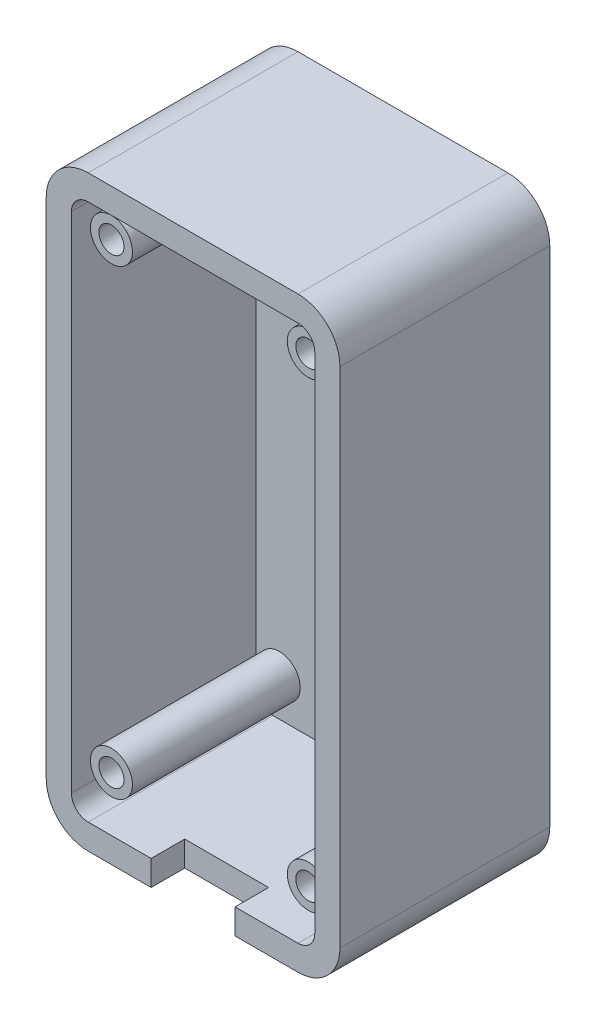
SolidWorks part; units mm, degrees
ref_plane "前视基准面" through (0, 0, 0) normal (0, 0, 1) x (1, 0, 0)
ref_plane "上视基准面" through (0, 0, 0) normal (0, 1, 0) x (1, 0, 0)
ref_plane "右视基准面" through (0, 0, 0) normal (1, 0, 0) x (0, 0, -1)
sketch "草图1" plane through (0, 0, 0) normal (0, 0, 1) x (1, 0, 0)
  line L1 (-193.4252, 70) -> (-168.4252, 70)
  line L2 (-198.4252, 65) -> (-198.4252, 5)
  line L3 (-193.4252, 0) -> (-168.4252, 0)
  line L4 (-163.4252, 65) -> (-163.4252, 5)
  line L5 (-198.4252, 70) -> (-163.4252, 0) construction
  line L6 (-198.4252, 0) -> (-163.4252, 70) construction
  arc A0 (-198.4252, 5) -> (-193.4252, 0) centre (-193.4252, 5) ccw
  arc A1 (-168.4252, 0) -> (-163.4252, 5) centre (-168.4252, 5) ccw
  arc A2 (-168.4252, 70) -> (-163.4252, 65) centre (-168.4252, 65) cw
  arc A3 (-193.4252, 70) -> (-198.4252, 65) centre (-193.4252, 65) ccw
  point P0 (-180.9252, 35)
  dimension "D3" = 5
  dimension "D1" = 70
  dimension "D2" = 35
extrude "凸台-拉伸1" add sketch "草图1" along normal blind 25
shell "抽壳2" thickness 3
sketch "草图3" plane through (0, 0, 3) normal (0, 0, 1) x (1, 0, 0)
  line L0 (-124.8248, 35) -> (-208.0256, 35) construction
  line L1 (-180.9252, 64.1908) -> (-180.9252, 32.4467) construction
  circle A0 centre (-192.6567, 62.5) radius 2.5
  circle A1 centre (-192.6567, 7.5) radius 2.5
  circle A2 centre (-169.1937, 62.5) radius 2.5
  circle A3 centre (-169.1937, 7.5) radius 2.5
  point P13 (-166.4252, 35)
  point P14 (-166.4252, 35)
  dimension "D1" = 5
  dimension "D2" = 55
extrude "凸台-拉伸4" add sketch "草图3" along normal blind 20
sketch "草图4" plane through (0, 0, 3) normal (0, 0, 1) x (1, 0, 0)
  circle A0 centre (-192.6567, 62.5) radius 1.5
  circle A1 centre (-169.1937, 62.5) radius 1.5
  circle A2 centre (-169.1937, 7.5) radius 1.5
  circle A3 centre (-192.6567, 7.5) radius 1.5
  dimension "D1" = 3
extrude "切除-拉伸4" cut sketch "草图4" against normal through all and the other way through all
sketch "草图6" plane through (0, 0, 0) normal (0, 1, 0) x (1, 0, 0)
  line L0 (-180.9252, -42.9125) -> (-180.9252, -7.0875) construction
  line L2 (-180.9252, -25) -> (-175.9252, -25)
  line L3 (-168.4252, -25) -> (-193.4252, -25) construction
  line L4 (-175.9252, -25) -> (-175.9252, -21)
  line L5 (-175.9252, -21) -> (-185.9252, -21)
  line L6 (-185.9252, -21) -> (-185.9252, -25)
  line L7 (-185.9252, -25) -> (-180.9252, -25)
  point P3 (-180.9252, -25)
  dimension "D1" = 10
  dimension "D2" = 4
extrude "切除-拉伸10" cut sketch "草图6" against normal through all and the other way blind 5
